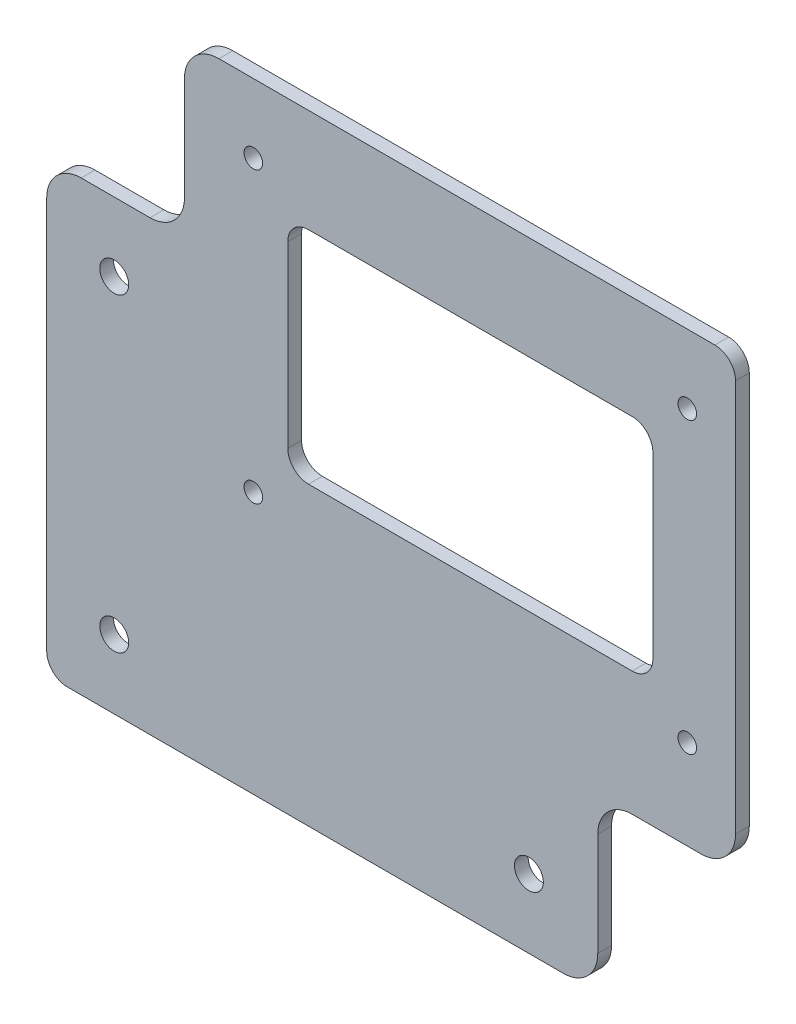
SolidWorks part; units mm, degrees
material "C-玻璃纤维"
ref_plane "前视基准面" through (0, 0, 0) normal (0, 0, 1) x (1, 0, 0)
ref_plane "上视基准面" through (0, 0, 0) normal (0, 1, 0) x (1, 0, 0)
ref_plane "右视基准面" through (0, 0, 0) normal (1, 0, 0) x (0, 0, -1)
sketch "草图1" plane through (0, 0, 0) normal (0, 0, 1) x (1, 0, 0)
  line L1 (0, 0) -> (100, 0)
  line L2 (0, 0) -> (0, 90)
  line L3 (0, 90) -> (100, 90)
  line L4 (100, 0) -> (100, 90)
  dimension "D1" = 90
  dimension "D2" = 100
extrude "凸台-拉伸1" add sketch "草图1" along normal blind 2
sketch "草图2" plane through (0, 0, 2) normal (0, 0, 1) x (1, 0, 0)
  line L0 (0, 10) -> (100, 10) construction
  line L1 (0, 90) -> (0, 0) construction
  line L2 (100, 0) -> (100, 90) construction
  line L3 (0, 0) -> (100, 0) construction
  circle A0 centre (9.8, 10) radius 2.1
  circle A3 centre (70, 10) radius 2.1
  circle A4 centre (9.8, 55) radius 2.1
  dimension "D2" = 4.2
  dimension "D5" = 45
  dimension "D1" = 10
  dimension "D3" = 9.8
  dimension "D4" = 30
extrude "切除-拉伸1" cut sketch "草图2" against normal through all
sketch "草图3" plane through (0, 0, 2) normal (0, 0, 1) x (1, 0, 0)
  line L1 (100, 90) -> (0, 90) construction
  line L2 (0, 90) -> (0, 0) construction
  line L3 (38, 75) -> (85, 75)
  line L4 (35, 72) -> (35, 46)
  line L5 (38, 43) -> (85, 43)
  line L6 (88, 72) -> (88, 46)
  circle A0 centre (30, 80) radius 1.35
  circle A1 centre (93, 80) radius 1.35
  circle A2 centre (93, 38) radius 1.35
  circle A3 centre (30, 38) radius 1.35
  arc A4 (38, 43) -> (35, 46) centre (38, 46) cw
  arc A5 (85, 43) -> (88, 46) centre (85, 46) ccw
  arc A6 (88, 72) -> (85, 75) centre (85, 72) ccw
  arc A7 (38, 75) -> (35, 72) centre (38, 72) ccw
  point P13 (88, 43)
  point P23 (88, 75)
  point P26 (35, 75)
  dimension "D1" = 2.7
  dimension "D10" = 3
  dimension "D6" = 10
  dimension "D2" = 42
  dimension "D3" = 63
  dimension "D4" = 5
  dimension "D5" = 5
  dimension "D7" = 32
  dimension "D8" = 30
  dimension "D9" = 53
extrude "切除-拉伸2" cut sketch "草图3" against normal through all
fillet "圆角1" radius 3 4 edges at (0, 90, 1) (100, 90, 1) (100, 0, 1) (0, 0, 1)
sketch "草图5" plane through (0, 0, 2) normal (0, 0, 1) x (1, 0, 0)
  line L0 (100, 3) -> (100, 87) construction
  line L1 (0, 90) -> (20, 90)
  line L2 (0, 90) -> (0, 65)
  line L3 (0, 65) -> (20, 65)
  line L4 (20, 90) -> (20, 65)
  line L5 (100, 25) -> (80, 25)
  line L6 (100, 25) -> (100, 0)
  line L7 (100, 0) -> (80, 0)
  line L8 (80, 25) -> (80, 0)
  line L9 (3, 0) -> (97, 0) construction
  line L10 (97, 90) -> (3, 90) construction
  dimension "D1" = 25
  dimension "D2" = 25
  dimension "D3" = 20
  dimension "D4" = 20
extrude "切除-拉伸3" cut sketch "草图5" against normal blind 10
fillet "圆角2" radius 5 6 edges at (80, 0, 1) (100, 25, 1) (80, 25, 1) (20, 90, 1) (20, 65, 1) (0, 65, 1)
